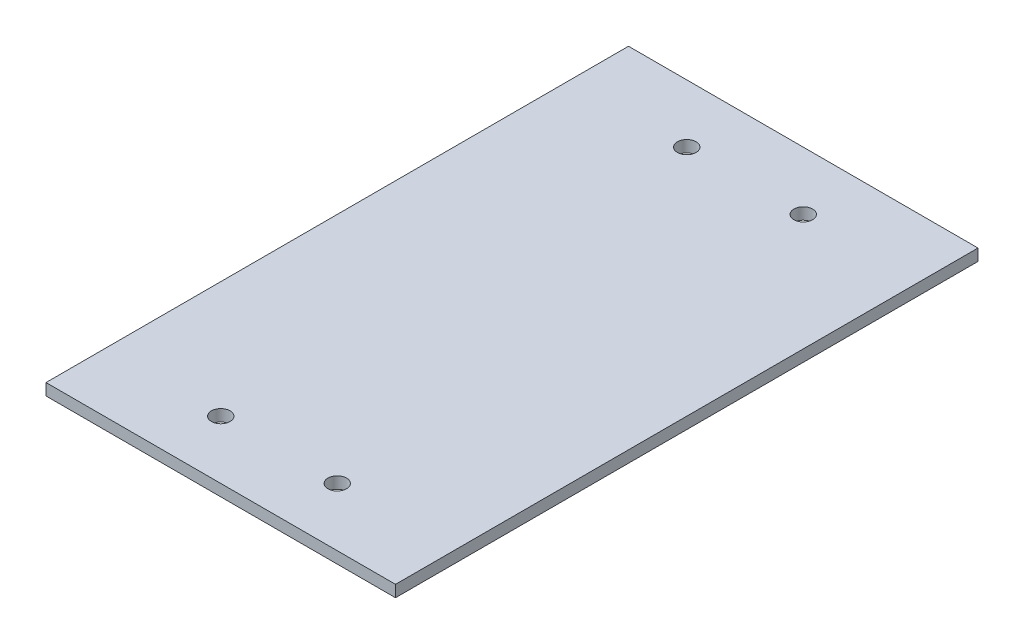
SolidWorks part; units mm, degrees
ref_plane "前视基准面" through (0, 0, 0) normal (0, 0, 1) x (1, 0, 0)
ref_plane "上视基准面" through (0, 0, 0) normal (0, 1, 0) x (1, 0, 0)
ref_plane "右视基准面" through (0, 0, 0) normal (1, 0, 0) x (0, 0, -1)
sketch "草图1" plane through (0, 0, 0) normal (0, 1, 0) x (1, 0, 0)
  line L1 (-30, -50) -> (30, -50)
  line L2 (-30, -50) -> (-30, 50)
  line L3 (-30, 50) -> (30, 50)
  line L4 (30, -50) -> (30, 50)
  line L5 (-30, -50) -> (30, 50) construction
  line L6 (-30, 50) -> (30, -50) construction
  point P0 (0, 0)
  dimension "D1" = 100
  dimension "D2" = 60
extrude "凸台-拉伸1" add sketch "草图1" along normal blind 2
sketch "草图2" plane through (0, 2, 0) normal (0, 1, 0) x (1, 0, 0)
  line L0 (0, 42.1518) -> (0, -35.6451) construction
  line L1 (-36.9014, 0) -> (36.935, 0) construction
  circle A0 centre (-10, 40) radius 1.6
  circle A1 centre (-10, -40) radius 1.6
  circle A2 centre (10, -40) radius 1.6
  circle A3 centre (10, 40) radius 1.6
  dimension "D1" = 3.2
  dimension "D2" = 80
  dimension "D3" = 20
extrude "切除-拉伸1" cut sketch "草图2" against normal up to next
